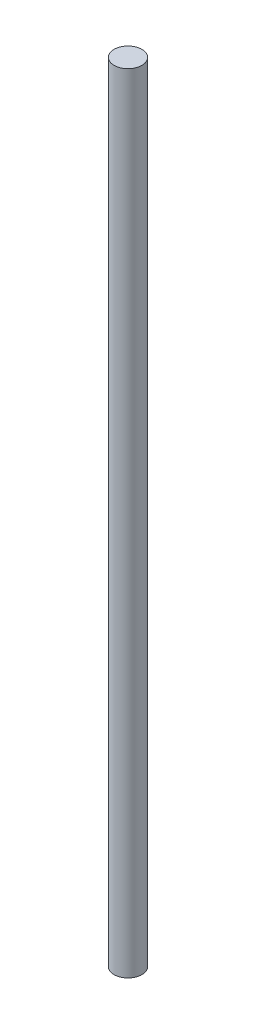
SolidWorks part; units mm, degrees
ref_plane "Front Plane" through (0, 0, 0) normal (0, 0, 1) x (1, 0, 0)
ref_plane "Top Plane" through (0, 0, 0) normal (0, 1, 0) x (1, 0, 0)
ref_plane "Right Plane" through (0, 0, 0) normal (1, 0, 0) x (0, 0, -1)
sketch "Sketch1" plane through (0, 0, 0) normal (0, 1, 0) x (1, 0, 0)
  circle A0 centre (0, 0) radius 6
  dimension "D1" = 12
extrude "Boss-Extrude1" add sketch "Sketch1" along normal blind 340
equation "\"d\"= 12"
equation "\"l\"= 340"
equation "\"D1@Boss-Extrude1\"=\"l\""
equation "\"D1@Sketch1\"=\"d\""
